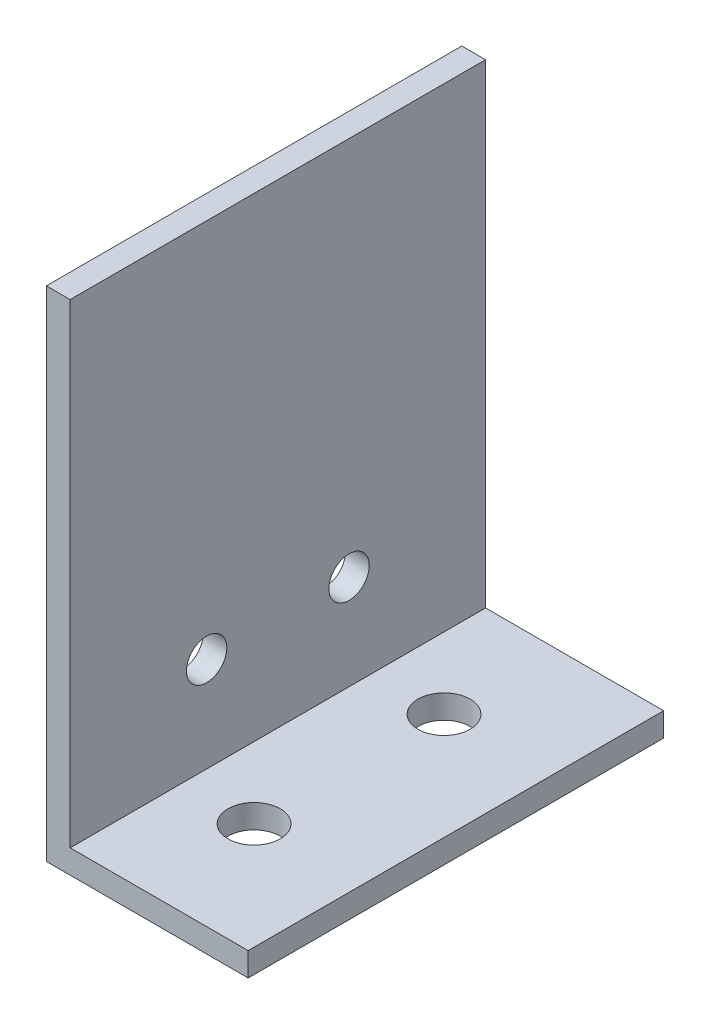
SolidWorks part; units mm, degrees
ref_plane "前视基准面" through (0, 0, 0) normal (0, 0, 1) x (1, 0, 0)
ref_plane "上视基准面" through (0, 0, 0) normal (0, 1, 0) x (1, 0, 0)
ref_plane "右视基准面" through (0, 0, 0) normal (1, 0, 0) x (0, 0, -1)
sketch "草图1" plane through (0, 0, 0) normal (0, 0, 1) x (1, 0, 0)
  line L0 (0, 0) -> (0, 42)
  line L1 (0, 42) -> (2, 42)
  line L2 (2, 42) -> (2, 2)
  line L3 (2, 2) -> (17, 2)
  line L4 (17, 2) -> (17, 0)
  line L5 (17, 0) -> (0, 0)
  dimension "D1" = 2
  dimension "D2" = 2
  dimension "D3" = 40
  dimension "D4" = 15
extrude "凸台-拉伸1" add sketch "草图1" along normal blind 35
sketch "草图2" plane through (0, 2, 0) normal (0, 1, 0) x (1, 0, 0)
  line L0 (-983, -17.5) -> (49017, -17.5) construction
  line L1 (17, -35) -> (17, 0) construction
  line L2 (2, -35) -> (2, 0) construction
  circle A0 centre (8, -9.5) radius 2.2
  circle A1 centre (8, -25.5) radius 2.2
  point P5 (17, -17.5)
  dimension "D1" = 4.4
  dimension "D2" = 16
  dimension "D3" = 6
extrude "切除-拉伸1" cut sketch "草图2" against normal up to next
sketch "草图3" plane through (0, 0, 0) normal (-1, 0, 0) x (0, 0, 1)
  line L0 (17.5, -1000) -> (17.5, 49000) construction
  line L1 (35, 0) -> (0, 0) construction
  circle A0 centre (11.5, 10) radius 1.7
  circle A1 centre (23.5, 10) radius 1.7
  point P5 (17.5, 0)
  dimension "D1" = 3.4
  dimension "D2" = 12
  dimension "D3" = 10
extrude "切除-拉伸2" cut sketch "草图3" against normal through all
